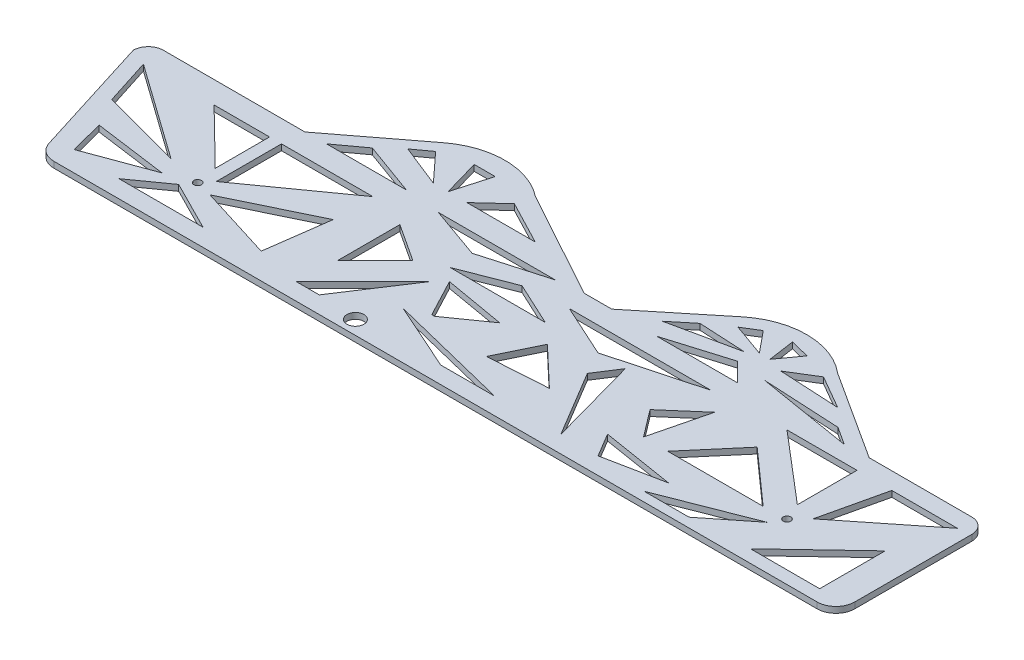
SolidWorks part; units mm, degrees
ref_plane "Front" through (0, 0, 0) normal (0, 0, 1) x (1, 0, 0)
ref_plane "Top" through (0, 0, 0) normal (0, 1, 0) x (1, 0, 0)
ref_plane "Right" through (0, 0, 0) normal (1, 0, 0) x (0, 0, -1)
sketch "Sketch1" plane through (0, 0, 0) normal (0, 1, 0) x (1, 0, 0)
  line L0 (0, 142) -> (42, 8)
  line L1 (0, 0) -> (444.5, 0)
  line L2 (0, 0) -> (0, 150)
  line L3 (0, 150) -> (444.5, 150)
  line L4 (444.5, 0) -> (444.5, 150)
  circle A0 centre (8, 142) radius 8
  circle A1 centre (50, 8) radius 8
  circle A2 centre (436.5, 142) radius 8
  circle A3 centre (436.5, 8) radius 8
  circle A5 centre (146.2694, 139.8404) radius 3.7162
  circle A6 centre (307.6065, 140.7106) radius 4.3136
  circle A8 centre (334.1065, 150.7981) radius 2.76
  circle A10 centre (77.8218, 98.3272) radius 2
  circle A11 centre (388.4758, 100.0771) radius 2
  circle A13 centre (182.4295, 77.3557) radius 4.5
  dimension "D3" = 8
  dimension "D5" = 8
  dimension "D7" = 8
  dimension "D9" = 8
  dimension "D1" = 150
  dimension "D2" = 444.5
  dimension "D4" = 8
  dimension "D6" = 50
  dimension "D8" = 8
  dimension "D10" = 8
extrude "Boss-Extrude1" add sketch "Sketch1" along normal blind 3.175 contours A3 L4 A2 L3 A0 L0 A1 L1 | A1 | A0 L0 | A2 | A3
sketch "Sketch2" plane through (0, 0, 0) normal (0, 0, 1) x (1, 0, 0)
  line L1 (-78.5546, 38.0306) -> (518.9117, 38.0306)
  line L2 (-78.5546, 38.0306) -> (-78.5546, -22.9419)
  line L3 (-78.5546, -22.9419) -> (518.9117, -22.9419)
  line L4 (518.9117, 38.0306) -> (518.9117, -22.9419)
extrude "Cut-Extrude1" cut sketch "Sketch2" against normal blind 70
fillet "Fillet1" radius 10 1 edges at (22.5672, 1.5875, -70)
fillet "Fillet2" radius 10 1 edges at (444.5, 1.5875, -70)
sketch "Sketch6" plane through (0, 0, 0) normal (0, 1, 0) x (1, 0, 0)
  circle A0 centre (149, 150.0404) radius 40
  dimension "D1" = 80
  dimension "D2" = 141
extrude "Boss-Extrude2" add sketch "Sketch6" along normal blind 3.175
sketch "Sketch7" plane through (0, 0, 0) normal (0, 1, 0) x (1, 0, 0)
  line L0 (124.1645, 181.3964) -> (82.7029, 149.7505)
  line L1 (173.8355, 181.3964) -> (231.4689, 149.7505)
  line L2 (82.7029, 149.7505) -> (231.4689, 149.7505)
  line L3 (124.1645, 181.3964) -> (173.8355, 181.3964)
  arc A0 (189, 150) -> (109, 150) centre (149, 150.0404) ccw construction
extrude "Boss-Extrude3" add sketch "Sketch7" along normal blind 3.175
sketch "Sketch9" plane through (0, 0, 0) normal (0, 1, 0) x (1, 0, 0)
  line L0 (444.5, 80) -> (444.5, 142) construction
  line L1 (231.0146, 150) -> (331.4643, 150) construction
  line L2 (283.7342, 181.0103) -> (245.6734, 150)
  line L3 (245.6734, 150) -> (269, 150)
  line L4 (334.2658, 181.0103) -> (397.5744, 150)
  circle A0 centre (309, 150) radius 40
  dimension "D1" = 135.5
  dimension "D2" = 0
extrude "Boss-Extrude4" add sketch "Sketch9" along normal blind 3.175 contours A0 L2 L3 | A0
sketch "Sketch12" plane through (0, 0, 0) normal (0, 1, 0) x (1, 0, 0)
  line L0 (326.1663, 186.1292) -> (382.1065, 150)
  line L1 (349, 150) -> (436.5, 150) construction
  line L2 (382.1065, 150) -> (340.3988, 150)
  line L3 (340.3988, 150) -> (326.1663, 186.1292)
  arc A0 (349, 150) -> (283.7342, 181.0103) centre (309, 150) ccw construction
extrude "Boss-Extrude6" add sketch "Sketch12" along normal blind 3.175
sketch "Sketch13" plane through (0, 3.175, 0) normal (0, 1, 0) x (1, 0, 0)
  line L0 (126.5966, 175.6996) -> (118.0714, 169.4738)
  line L1 (118.0714, 169.4738) -> (140.5908, 160.5209)
  line L2 (140.5908, 160.5209) -> (126.5966, 175.6996)
  line L3 (142.8058, 179.9554) -> (153.9245, 179.9554)
  line L4 (153.9245, 179.9554) -> (148.3652, 160.5209)
  line L5 (148.3652, 160.5209) -> (142.8058, 179.9554)
  line L6 (158.3698, 160.5209) -> (171.4569, 172.5867)
  line L7 (171.4569, 172.5867) -> (194.5942, 160.5209)
  line L8 (194.5942, 160.5209) -> (158.3698, 160.5209)
  line L9 (108.2238, 160.5209) -> (94.1772, 150.263)
  line L10 (94.1772, 150.263) -> (136.5126, 150.263)
  line L11 (136.5126, 150.263) -> (108.2238, 160.5209)
  line L12 (155.3245, 148.431) -> (192.4658, 148.431)
  line L13 (192.4658, 148.431) -> (217.2922, 148.431)
  line L14 (217.2922, 148.431) -> (183.0255, 138.6288)
  line L15 (183.0255, 138.6288) -> (155.3245, 148.431)
extrude "Cut-Extrude2" cut sketch "Sketch13" against normal blind 10
sketch "Sketch14" plane through (0, 3.175, 0) normal (0, 1, 0) x (1, 0, 0)
  line L0 (287.3874, 175.1903) -> (295.6681, 180.2928)
  line L1 (295.6681, 180.2928) -> (305.0159, 168.9003)
  line L2 (305.0159, 168.9003) -> (287.3874, 175.1903)
  line L3 (308.6301, 182.8347) -> (318.9001, 180.2928)
  line L4 (318.9001, 180.2928) -> (310.6308, 168.9003)
  line L5 (310.6308, 168.9003) -> (308.6301, 182.8347)
  line L6 (318.9001, 166.3792) -> (332.8972, 175.004)
  line L7 (332.8972, 175.004) -> (350.7508, 164.7029)
  line L8 (350.7508, 164.7029) -> (318.9001, 166.3792)
  line L9 (300.342, 165.541) -> (275.584, 166.8441)
  line L10 (275.584, 166.8441) -> (264.6077, 157.8377)
  line L11 (264.6077, 157.8377) -> (300.342, 165.541)
  line L12 (318.9001, 157.8377) -> (359.8594, 155.682)
  line L13 (359.8594, 155.682) -> (369.4561, 149.484)
  line L14 (369.4561, 149.484) -> (318.9001, 157.8377)
  line L15 (302.8297, 159.3997) -> (270.0958, 149.484)
  line L16 (270.0958, 149.484) -> (312.6977, 149.484)
  line L17 (312.6977, 149.484) -> (302.8297, 159.3997)
extrude "Cut-Extrude3" cut sketch "Sketch14" against normal blind 10
sketch "Sketch15" plane through (0, 3.175, 0) normal (0, 1, 0) x (1, 0, 0)
  line L0 (9.0825, 138.3329) -> (16.9518, 113.6667)
  line L1 (16.9518, 113.6667) -> (59.8472, 102.1982)
  line L2 (59.8472, 102.1982) -> (9.0825, 138.3329)
  line L3 (46.5273, 138.3329) -> (75.9328, 138.3329)
  line L4 (75.9328, 138.3329) -> (75.9328, 109.5522)
  line L5 (75.9328, 109.5522) -> (46.5273, 138.3329)
  line L7 (82.2752, 103.7657) -> (130.7264, 138.3329)
  line L9 (82.2752, 103.7657) -> (82.2752, 138.3329)
  line L10 (82.2752, 138.3329) -> (130.7264, 138.3329)
  line L11 (25.2521, 98.6201) -> (30.0142, 80.8004)
  line L12 (30.0142, 80.8004) -> (63.9237, 93.3265)
  line L13 (63.9237, 93.3265) -> (25.2521, 98.6201)
  line L14 (73.6517, 92.4621) -> (55.1531, 79.2644)
  line L15 (55.1531, 79.2644) -> (99.7556, 79.2644)
  line L16 (99.7556, 79.2644) -> (73.6517, 92.4621)
  line L17 (86.7036, 95.9733) -> (130.7264, 117.2609)
  line L18 (130.7264, 117.2609) -> (126.1316, 83.6947)
  line L19 (126.1316, 83.6947) -> (86.7036, 95.9733)
extrude "Cut-Extrude4" cut sketch "Sketch15" against normal blind 10
sketch "Sketch16" plane through (0, 3.175, 0) normal (0, 1, 0) x (1, 0, 0)
  line L0 (437.8922, 140.9946) -> (395.3069, 107.1133)
  line L1 (395.3069, 107.1133) -> (403.1214, 140.9946)
  line L2 (403.1214, 140.9946) -> (437.8922, 140.9946)
  line L3 (384.6548, 93.2682) -> (361.6552, 74.9694)
  line L4 (361.6552, 74.9694) -> (337.7987, 74.9694)
  line L5 (337.7987, 74.9694) -> (384.6548, 93.2682)
  line L6 (429.1069, 111.4834) -> (392.4602, 76.7623)
  line L7 (392.4602, 76.7623) -> (429.1069, 76.7623)
  line L8 (429.1069, 76.7623) -> (429.1069, 111.4834)
  line L9 (384.6548, 140.9946) -> (347.5515, 140.9946)
  line L10 (347.5515, 140.9946) -> (384.6548, 109.3929)
  line L11 (384.6548, 109.3929) -> (384.6548, 140.9946)
  line L12 (347.5515, 125.1937) -> (325.7464, 99.5925)
  line L13 (325.7464, 99.5925) -> (376.3076, 99.5925)
  line L14 (376.3076, 99.5925) -> (347.5515, 125.1937)
extrude "Cut-Extrude5" cut sketch "Sketch16" against normal blind 10
sketch "Sketch17" plane through (0, 3.175, 0) normal (0, 1, 0) x (1, 0, 0)
  line L0 (234.1464, 139.0261) -> (309.1978, 139.0261)
  line L1 (309.1978, 139.0261) -> (262.1188, 126.2677)
  line L2 (262.1188, 126.2677) -> (234.1464, 139.0261)
  line L3 (211.1557, 136.9624) -> (183.7273, 126.2677)
  line L4 (183.7273, 126.2677) -> (234.1464, 126.2677)
  line L5 (234.1464, 126.2677) -> (211.1557, 136.9624)
  line L6 (150.7106, 132.6469) -> (150.7106, 99.7426)
  line L7 (150.7106, 99.7426) -> (170.588, 119.62)
  line L8 (150.7106, 132.6469) -> (170.588, 119.62)
  line L9 (150.7106, 80.176) -> (184.5536, 114.019)
  line L10 (184.5536, 114.019) -> (161.6119, 79.0127)
  line L12 (149.369, 79.0127) -> (150.7106, 80.176)
  line L13 (161.6119, 79.0127) -> (149.369, 79.0127)
  line L14 (190.0223, 95.0326) -> (225.9967, 79.0127)
  line L15 (225.9967, 79.0127) -> (254.5452, 79.0127)
  line L16 (254.5452, 79.0127) -> (190.0223, 95.0326)
  line L17 (200.5274, 99.7426) -> (190.0223, 119.62)
  line L18 (190.0223, 119.62) -> (222.2837, 114.019)
  line L19 (222.2837, 114.019) -> (202.0088, 99.7426)
  line L20 (202.0088, 99.7426) -> (200.5274, 99.7426)
  line L21 (244.7272, 116.8195) -> (234.1464, 95.0326)
  line L22 (234.1464, 95.0326) -> (265.5076, 97.0975)
  line L23 (265.5076, 97.0975) -> (244.7272, 116.8195)
  line L24 (268.7176, 114.019) -> (289.6557, 79.0127)
  line L25 (289.6557, 79.0127) -> (276.5699, 126.2677)
  line L26 (276.5699, 126.2677) -> (268.7176, 114.019)
  line L27 (301.9298, 114.019) -> (320.2625, 129.9155)
  line L28 (320.2625, 129.9155) -> (312.7711, 99.7426)
  line L29 (312.7711, 99.7426) -> (301.9298, 114.019)
  line L30 (301.9298, 91.5099) -> (309.4046, 79.0127)
  line L31 (309.4046, 79.0127) -> (340.5354, 85.2613)
  line L32 (340.5354, 85.2613) -> (301.9298, 91.5099)
extrude "Cut-Extrude6" cut sketch "Sketch17" against normal blind 10
